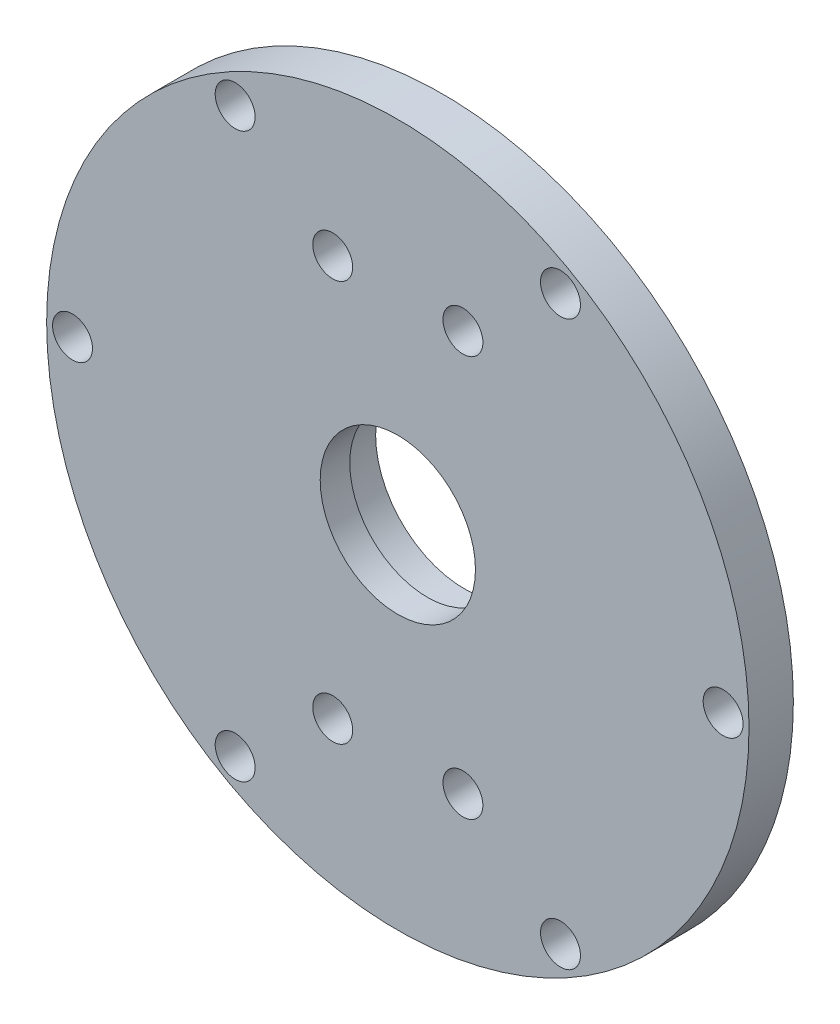
SolidWorks part; units mm, degrees
ref_plane "Front Plane" through (0, 0, 0) normal (0, 0, 1) x (1, 0, 0)
ref_plane "Top Plane" through (0, 0, 0) normal (0, 1, 0) x (1, 0, 0)
ref_plane "Right Plane" through (0, 0, 0) normal (1, 0, 0) x (0, 0, -1)
sketch "Sketch1" plane through (0, 0, 0) normal (0, 0, 1) x (1, 0, 0)
  circle A0 centre (0, 0) radius 47.5
  circle A1 centre (0, 0) radius 10.5
  circle A3 centre (0, 0) radius 44 construction
  circle A4 centre (44, 0) radius 2.7
  circle A5 centre (22, -38.1051) radius 2.7
  circle A6 centre (-22, -38.1051) radius 2.7
  circle A7 centre (-44, 0) radius 2.7
  circle A8 centre (-22, 38.1051) radius 2.7
  circle A9 centre (22, 38.1051) radius 2.7
  point P20 (0, 0)
  dimension "D1" = 95
  dimension "D2" = 21
  dimension "D3" = 3.5
  dimension "D4" = 5.4
  dimension "D5" = 6
extrude "Boss-Extrude1" add sketch "Sketch1" along normal blind 6
sketch "Sketch2" plane through (0, 0, 0) normal (0, 0, -1) x (-1, 0, 0)
  circle A0 centre (0, 0) radius 12
  dimension "D1" = 24
extrude "Cut-Extrude1" cut sketch "Sketch2" against normal blind 2 contours A0
sketch "Sketch3" plane through (0, 0, 0) normal (0, 0, -1) x (-1, 0, 0)
  circle A0 centre (0, 0) radius 12 construction
  circle A1 centre (0, 0) radius 12
  circle A2 centre (0, 0) radius 16
  dimension "D1" = 4
extrude "Boss-Extrude2" add sketch "Sketch3" along normal blind 3
sketch "Sketch4" plane through (0, 0, 6) normal (0, 0, 1) x (1, 0, 0)
  line L0 (0, 0) -> (0, 28.5) construction
  line L1 (0, 0) -> (28.5, 0) construction
  line L2 (0, 0) -> (8.807, 27.1051) construction
  circle A0 centre (0, 0) radius 28.5 construction
  circle A1 centre (8.807, 27.1051) radius 2.7
  circle A2 centre (-8.807, 27.1051) radius 2.7
  circle A3 centre (8.807, -27.1051) radius 2.7
  circle A4 centre (-8.807, -27.1051) radius 2.7
  dimension "D1" = 57
  dimension "D3" = 5.4
  dimension "D2" = 18
extrude "Cut-Extrude2" cut sketch "Sketch4" against normal blind 5
